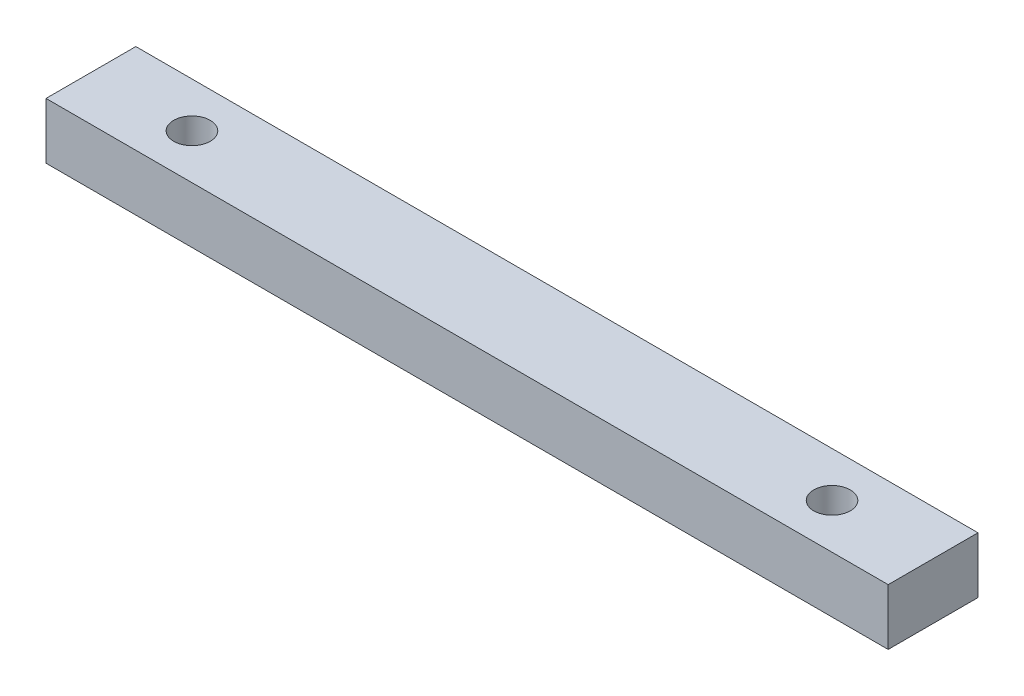
SolidWorks part; units mm, degrees
ref_plane "Front Plane" through (0, 0, 0) normal (0, 0, 1) x (1, 0, 0)
ref_plane "Top Plane" through (0, 0, 0) normal (0, 1, 0) x (1, 0, 0)
ref_plane "Right Plane" through (0, 0, 0) normal (1, 0, 0) x (0, 0, -1)
sketch "Sketch1" plane through (0, 0, 0) normal (0, 1, 0) x (1, 0, 0)
  line L0 (-75, -8) -> (75, 8) construction
  line L1 (-75, -8) -> (75, -8)
  line L2 (-75, -8) -> (-75, 8)
  line L3 (-75, 8) -> (75, 8)
  line L4 (75, -8) -> (75, 8)
  point P4 (0, 0)
  dimension "D1" = 16
  dimension "D2" = 150
extrude "Boss-Extrude1" add sketch "Sketch1" along normal blind 10
sketch "Sketch2" plane through (0, 10, 0) normal (0, 1, 0) x (1, 0, 0)
  line L0 (-75, 0) -> (-57, 0) construction
  line L1 (-75, 8) -> (-75, -8) construction
  line L2 (0, 0) -> (0, 29.0079) construction
  circle A0 centre (-57, 0) radius 3.25
  circle A1 centre (57, 0) radius 3.25
  dimension "D1" = 6.5
  dimension "D2" = 14.75
extrude "Cut-Extrude1" cut sketch "Sketch2" against normal up to next
